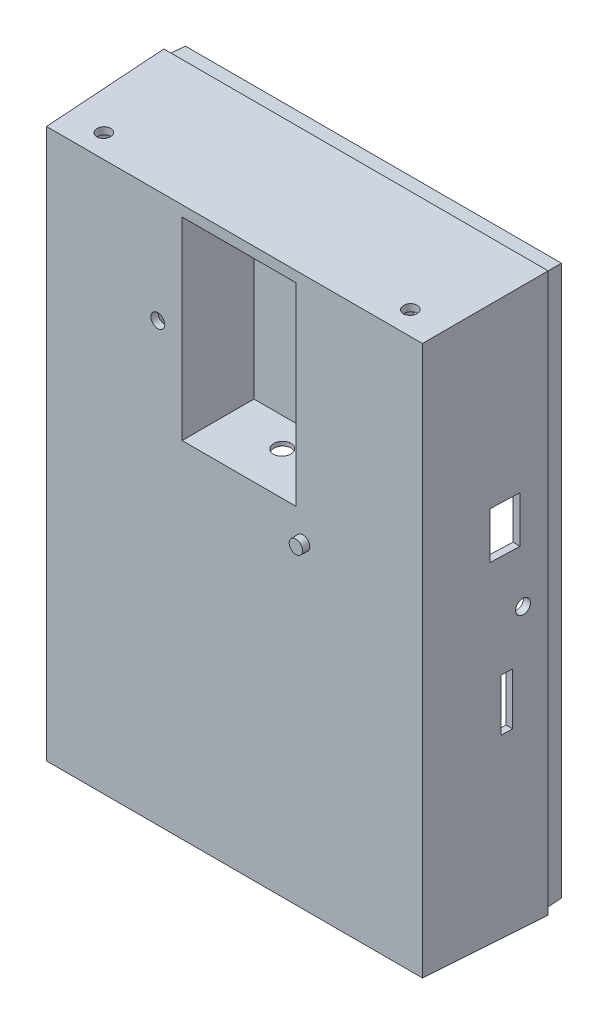
SolidWorks part; units mm, degrees
ref_plane "Front Plane" through (0, 0, 0) normal (0, 0, 1) x (1, 0, 0)
ref_plane "Top Plane" through (0, 0, 0) normal (0, 1, 0) x (1, 0, 0)
ref_plane "Right Plane" through (0, 0, 0) normal (1, 0, 0) x (0, 0, -1)
sketch "Sketch1" plane through (-178.9356, -87.8276, -1672.8765) normal (0, 0, 1) x (1, 0, 0)
  line L0 (27.3099, 6.0084) -> (138.0083, 6.0084) construction
  line L1 (138.0083, 6.0084) -> (138.0083, 166.7068) construction
  line L2 (138.0083, 166.7068) -> (27.3099, 166.7068) construction
  line L3 (27.3099, 166.7068) -> (27.3099, 6.0084) construction
  line L4 (27.3099, 6.0084) -> (138.0083, 6.0084)
  line L5 (138.0083, 6.0084) -> (138.0083, 166.7068)
  line L6 (138.0083, 166.7068) -> (27.3099, 166.7068)
  line L7 (27.3099, 166.7068) -> (27.3099, 6.0084)
extrude "Boss-Extrude1" add sketch "Sketch1" along normal blind 35 draft 2
shell "Shell1" thickness 2
sketch "Sketch9" plane through (0, 0, -1639.8765) normal (0, 0, -1) x (-1, 0, 0)
  line L0 (44.081, 75.7256) -> (148.4722, 75.7256) construction
  line L1 (77.4722, 75.7256) -> (112.4722, 75.7256)
  line L2 (77.4722, 75.7256) -> (77.4722, 17.7256)
  line L3 (77.4722, 17.7256) -> (112.4722, 17.7256)
  line L4 (112.4722, 75.7256) -> (112.4722, 17.7256)
  line L5 (148.4722, 75.7256) -> (148.4722, -78.6656) construction
  dimension "D1" = 58
  dimension "D2" = 35
  dimension "D3" = 36
extrude "Boss-Extrude5" add sketch "Sketch9" along normal blind 32 draft 2
sketch "Sketch6" plane through (-99.2245, 0, -3.465) normal (0.9994, 0, 0.0349) x (0.0349, 0, -0.9994)
  line L0 (1635.4078, -80.597) -> (1635.4078, 77.657) construction
  line L1 (1657.3178, -30.597) -> (1660.5178, -30.597)
  line L2 (1657.3178, -30.597) -> (1657.3178, -15.597)
  line L3 (1657.3178, -15.597) -> (1660.5178, -15.597)
  line L4 (1660.5178, -30.597) -> (1660.5178, -15.597)
  line L5 (1657.3178, -30.597) -> (1660.5178, -15.597) construction
  line L6 (1657.3178, -15.597) -> (1660.5178, -30.597) construction
  point P0 (1658.9178, -23.097)
  dimension "D1" = 15
  dimension "D2" = 3.2
  dimension "D3" = 50
  dimension "D4" = 23.51
extrude "Cut-Extrude3" cut sketch "Sketch6" against normal up to next (2 mm away) draft 2 draft outward yes
sketch "Sketch11" plane through (0, 0, -1637.8765) normal (0, 0, 1) x (1, 0, 0)
  line L1 (-111.3547, 74.6081) -> (-78.5896, 74.6081)
  line L2 (-111.3547, 74.6081) -> (-111.3547, 18.8431)
  line L3 (-111.3547, 18.8431) -> (-78.5896, 18.8431)
  line L4 (-78.5896, 74.6081) -> (-78.5896, 18.8431)
extrude "Cut-Extrude4" cut sketch "Sketch11" against normal blind 20 draft 2
sketch "Sketch13" plane through (0, -39.492, -1.3791) normal (0, -0.9994, -0.0349) x (1, 0, 0)
  line L0 (-77.4722, -1639.4962) -> (-112.4722, -1639.4962) construction
  circle A0 centre (-94.4722, -1649.4962) radius 2.5
  dimension "D1" = 5
  dimension "D2" = 10
  dimension "D3" = 17
extrude "Cut-Extrude5" cut sketch "Sketch13" against normal up to next (1.1866 mm away) draft 2 draft outward yes
sketch "Sketch14" plane through (0, 0, -1639.8765) normal (0, 0, -1) x (-1, 0, 0)
  line L0 (59.0793, -3.6656) -> (119.0793, -3.6656) construction
  line L1 (119.0793, -3.6656) -> (119.0793, -43.6656) construction
  line L2 (119.0793, -43.6656) -> (59.0793, -43.6656) construction
  line L3 (59.0793, -3.6656) -> (59.0793, -43.6656) construction
  line L4 (148.4722, -78.6656) -> (44.081, -78.6656) construction
  line L5 (44.081, -78.6656) -> (44.081, 75.7256) construction
  circle A0 centre (59.0793, -3.6656) radius 4
  circle A1 centre (59.0793, -43.6656) radius 4
  circle A2 centre (119.0793, -3.6656) radius 4
  circle A3 centre (119.0793, -43.6656) radius 4
  dimension "D1" = 8
  dimension "D2" = 8
  dimension "D3" = 8
  dimension "D4" = 8
  dimension "D5" = 60
  dimension "D6" = 40
  dimension "D7" = 35
  dimension "D8" = 14.9983
extrude "Boss-Extrude6" add sketch "Sketch14" along normal blind 18 draft 2
sketch "Sketch15" plane through (0, 0, -1657.8765) normal (0, 0, -1) x (-1, 0, 0)
  circle A0 centre (59.0793, -3.6656) radius 2
  circle A1 centre (119.0793, -3.6656) radius 2
  circle A2 centre (119.0793, -43.6656) radius 2
  circle A3 centre (59.0793, -43.6656) radius 2
  dimension "D1" = 4
  dimension "D2" = 4
  dimension "D3" = 4
  dimension "D4" = 4
extrude "Cut-Extrude6" cut sketch "Sketch15" against normal blind 5 draft 2
sketch "Sketch17" plane through (0, 0, -1672.8765) normal (0, 0, -1) x (-1, 0, 0)
  line L0 (149.6246, -79.818) -> (42.9286, -79.818) construction
  line L1 (149.6246, 76.878) -> (149.6246, -79.818) construction
  line L2 (42.9286, -79.818) -> (42.9286, 76.878) construction
  line L3 (42.9286, 76.878) -> (149.6246, 76.878) construction
  line L4 (149.6246, -79.818) -> (42.9286, -79.818)
  line L5 (149.6246, 76.878) -> (149.6246, -79.818)
  line L6 (42.9286, -79.818) -> (42.9286, 76.878)
  line L7 (42.9286, 76.878) -> (149.6246, 76.878)
  line L8 (41.9286, 77.878) -> (150.6246, 77.878)
  line L9 (150.6246, 77.878) -> (150.6246, -80.818)
  line L10 (150.6246, -80.818) -> (41.9286, -80.818)
  line L11 (41.9286, -80.818) -> (41.9286, 77.878)
  dimension "D1" = 1
extrude "Boss-Extrude8" add sketch "Sketch17" along normal blind 5 draft 2
sketch "Sketch18" plane through (0, 0, -1637.8765) normal (0, 0, 1) x (1, 0, 0)
  line L0 (-111.3547, 18.8431) -> (-78.5896, 18.8431) construction
  line L1 (-78.5896, 18.8431) -> (-78.5896, 74.6081) construction
  circle A0 centre (-76.5896, 10.7256) radius 2
  dimension "D1" = 4
  dimension "D2" = 8.1175
  dimension "D3" = 2
extrude "Boss-Extrude9" add sketch "Sketch18" along normal blind 2 draft 2
sketch "Sketch19" plane through (0, 0, -1637.8765) normal (0, 0, 1) x (1, 0, 0)
  line L0 (-111.3547, 18.8431) -> (-78.5896, 18.8431) construction
  line L1 (-111.3547, 74.6081) -> (-111.3547, 18.8431) construction
  circle A0 centre (-118.3547, 45.2431) radius 2
  dimension "D1" = 4
  dimension "D2" = 26.4
  dimension "D3" = 7
extrude "Cut-Extrude7" cut sketch "Sketch19" against normal up to next (2 mm away) draft 2
sketch "Sketch26" plane through (-91.0953, 0, 3.1811) normal (0.9994, 0, -0.0349) x (-0.0349, 0, -0.9994)
  circle A1 centre (1670.1491, -1.47) radius 2
  circle A2 centre (1670.1491, -1.47) radius 2
  dimension "D1" = 0
extrude "Cut-Extrude11" cut sketch "Sketch26" against normal up to next (2 mm away) draft 2 draft outward yes
sketch "Sketch27" plane through (-101.2233, 0, -3.5348) normal (-0.9994, 0, -0.0349) x (-0.0349, 0, 0.9994)
  circle A1 centre (-1663.4291, -1.47) radius 2
  circle A2 centre (-1663.4291, -1.47) radius 2
  dimension "D1" = 0
extrude "Cut-Extrude12" cut sketch "Sketch27" against normal up to next (2 mm away) draft 2 draft outward yes
sketch "Sketch29" plane through (-93.0941, 0, 3.2509) normal (-0.9994, 0, 0.0349) x (0.0349, 0, 0.9994)
  line L0 (-1677.1491, 78.8792) -> (-1677.1491, -81.8192) construction
  circle A0 centre (-1662.1491, -30.597) radius 6
  dimension "D2" = 12
  dimension "D1" = 15
  dimension "D3" = 50
extrude "Cut-Extrude15" cut sketch "Sketch29" against normal blind 10 draft 2 draft outward yes
sketch "Sketch32" plane through (-99.2245, 0, -3.465) normal (0.9994, 0, 0.0349) x (0.0349, 0, -0.9994)
  line L0 (1670.4291, -81.8192) -> (1670.4291, 78.8792) construction
  line L1 (1662.5791, 13.957) -> (1654.2791, 13.957)
  line L2 (1662.5791, 13.957) -> (1662.5791, 27.357)
  line L3 (1662.5791, 27.357) -> (1654.2791, 27.357)
  line L4 (1654.2791, 13.957) -> (1654.2791, 27.357)
  line L5 (1662.5791, 13.957) -> (1654.2791, 27.357) construction
  line L6 (1662.5791, 27.357) -> (1654.2791, 13.957) construction
  point P0 (1658.4291, 20.657)
  dimension "D1" = 8.3
  dimension "D2" = 13.4
  dimension "D3" = 12
  dimension "D4" = 57
extrude "Cut-Extrude16" cut sketch "Sketch32" against normal up to next (2 mm away) draft 2
sketch "Sketch34" plane through (0, 20.4361, 0.7136) normal (0, 0.9994, 0.0349) x (1, 0, 0)
  line L0 (-42.1496, 1639.5889) -> (-150.4035, 1639.5889) construction
  circle A0 centre (-140.4035, 1646.0889) radius 2
  circle A1 centre (-52.1496, 1646.0889) radius 2
  dimension "D1" = 4
  dimension "D2" = 4
  dimension "D3" = 6.5
  dimension "D4" = 6.5
  dimension "D5" = 10
  dimension "D6" = 10
extrude "Cut-Extrude17" cut sketch "Sketch34" against normal up to next (2 mm away) draft 2
scale "Scale1"
other "Parting Line2"
other "Parting Surface2" parameters "D1"=50
sketch "Sketch28" plane through (0, 0, -1682.7469) normal (0, 0, 1) x (1, 0, 0)
  line L1 (17.5531, 131.7307) -> (-209.2065, 131.7307)
  line L2 (17.5531, 131.7307) -> (17.5531, -148.2693)
  line L3 (17.5531, -148.2693) -> (-209.2065, -148.2693)
  line L4 (-209.2065, 131.7307) -> (-209.2065, -148.2693)
  line L5 (17.5531, 131.7307) -> (-209.2065, -148.2693) construction
  line L6 (17.5531, -148.2693) -> (-209.2065, 131.7307) construction
  point P0 (-95.8267, -8.2693)
  dimension "D1" = 280
  dimension "D2" = 226.7596
  dimension "D3" = 17.5531
  dimension "D4" = 131.7307
